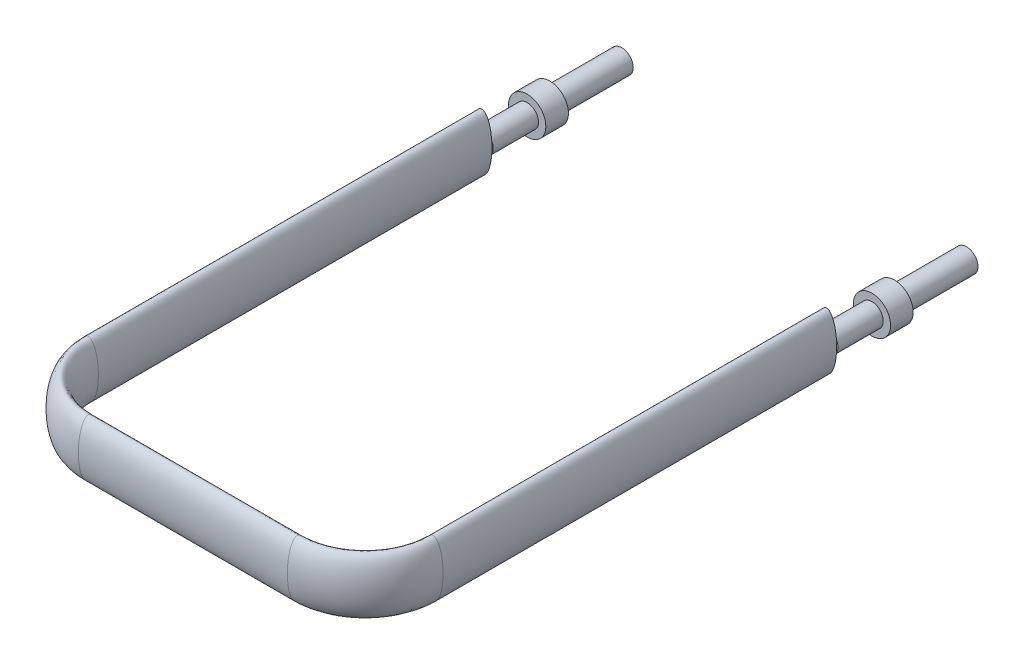
SolidWorks part; units mm, degrees
ref_plane "Front Plane" through (0, 0, 0) normal (0, 0, 1) x (1, 0, 0)
ref_plane "Top Plane" through (0, 0, 0) normal (0, 1, 0) x (1, 0, 0)
ref_plane "Right Plane" through (0, 0, 0) normal (1, 0, 0) x (0, 0, -1)
sketch "Sketch1" plane through (0, 0, 0) normal (0, 0, 1) x (1, 0, 0)
  line L0 (0, 0) -> (-7.62, 0) construction
  line L1 (0, 0) -> (7.62, 0) construction
  circle A0 centre (-7.62, 0) radius 0.51
  circle A1 centre (7.62, 0) radius 0.51
  dimension "D1" = 1.02
  dimension "D2" = 15.24
extrude "Boss-Extrude1" add sketch "Sketch1" against normal blind 3.18
sketch "Sketch2" plane through (0, 0, 0) normal (0, 0, 1) x (1, 0, 0)
  circle A0 centre (-7.62, 0) radius 0.825
  circle A1 centre (7.62, 0) radius 0.825
  dimension "D1" = 1.65
extrude "Boss-Extrude2" add sketch "Sketch2" along normal blind 1
sketch "Sketch3" plane through (0, 0, 1) normal (0, 0, 1) x (1, 0, 0)
  circle A0 centre (-7.62, 0) radius 0.5
  circle A1 centre (7.62, 0) radius 0.5
  dimension "D1" = 1
extrude "Boss-Extrude3" add sketch "Sketch3" along normal blind 2
sketch "Sketch4" plane through (0, 0, 0) normal (0, 1, 0) x (1, 0, 0)
  line L0 (7.12, -3) -> (8.12, -3) construction
  line L1 (-8.12, -3) -> (-7.12, -3) construction
  line L2 (7.12, -3) -> (8.12, -3) construction
  line L3 (-8.12, -3) -> (-7.12, -3) construction
  line L4 (-7.62, -3) -> (-7.62, -20.4)
  line L5 (7.62, -3) -> (7.62, -20.4)
  line L6 (4.62, -23.4) -> (-4.62, -23.4)
  arc A0 (4.62, -23.4) -> (7.62, -20.4) centre (4.62, -20.4) ccw
  arc A1 (-4.62, -23.4) -> (-7.62, -20.4) centre (-4.62, -20.4) cw
  dimension "D2" = 3
  dimension "D1" = 20.4
sketch "Sketch5" plane through (0, 0, 3) normal (0, 0, 1) x (1, 0, 0)
  line L0 (-7.62, 1.25) -> (-7.62, -1.25) construction
  ellipse E0 centre (-7.62, 0) end of major axis (-7.62, -1.25) minor radius 0.4444
  dimension "D1" = 2.5
sweep "Sweep1" add profiles "Sketch5" path "Sketch4"
